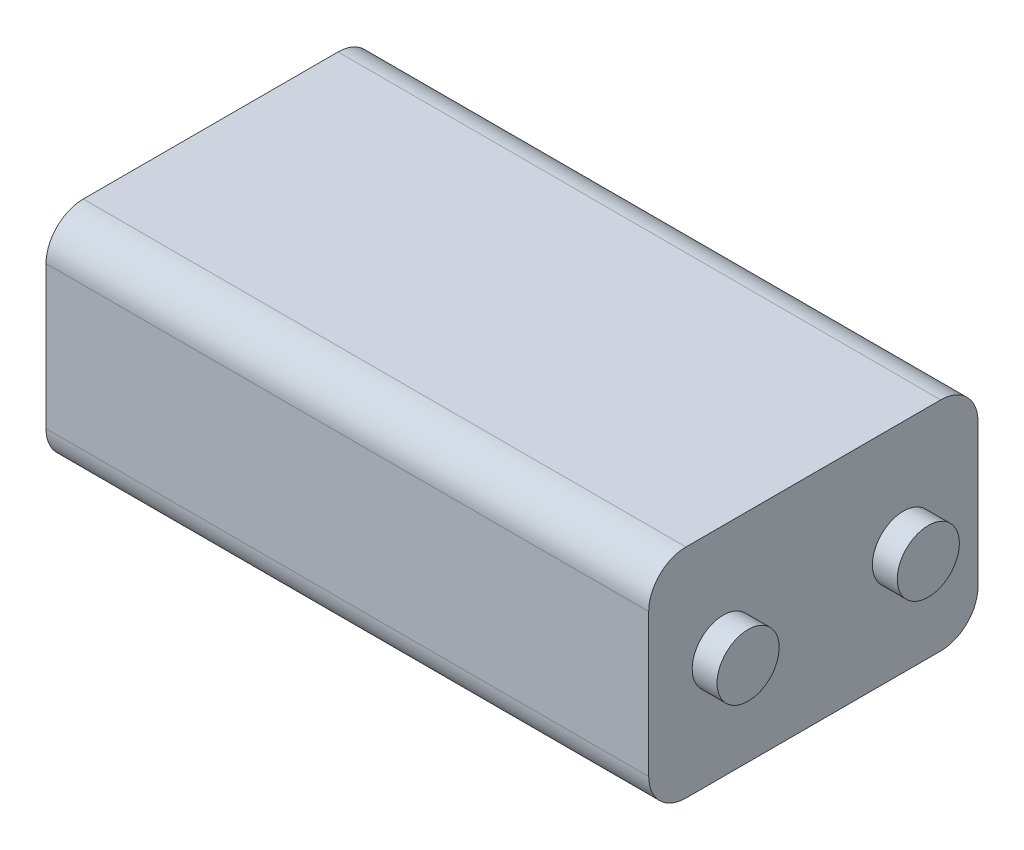
SolidWorks part; units mm, degrees
ref_plane "正面" through (0, 0, 0) normal (0, 0, 1) x (1, 0, 0)
ref_plane "平面" through (0, 0, 0) normal (0, 1, 0) x (1, 0, 0)
ref_plane "右側面" through (0, 0, 0) normal (1, 0, 0) x (0, 0, -1)
sketch "ｽｹｯﾁ1" plane through (0, 0, 0) normal (0, 0, 1) x (1, 0, 0)
  line L1 (-24.25, 8.75) -> (24.25, 8.75)
  line L2 (-24.25, 8.75) -> (-24.25, -8.75)
  line L3 (-24.25, -8.75) -> (24.25, -8.75)
  line L4 (24.25, 8.75) -> (24.25, -8.75)
  line L5 (-24.25, 8.75) -> (24.25, -8.75) construction
  line L6 (-24.25, -8.75) -> (24.25, 8.75) construction
  point P0 (0, 0)
  dimension "D1" = 48.5
  dimension "D2" = 17.5
extrude "ﾎﾞｽ - 押し出し1" add sketch "ｽｹｯﾁ1" along normal blind 26.5
fillet "ﾌｨﾚｯﾄ1" radius 3 4 edges at (0, -8.75, 26.5) (0, -8.75, 0) (0, 8.75, 0) (0, 8.75, 26.5)
sketch "ｽｹｯﾁ2" plane through (24.25, 0, 0) normal (1, 0, 0) x (0, 0, -1)
  line L0 (-26.5, -5.75) -> (-26.5, 5.75) construction
  line L1 (0, -5.75) -> (0, 5.75) construction
  circle A0 centre (-20.5, 0) radius 2.5
  circle A1 centre (-6, 0) radius 2.5
  point P6 (-26.5, 0)
  dimension "D1" = 6
  dimension "D2" = 6
  dimension "D5" = 5
  dimension "D6" = 5
  dimension "D3" = 0
  dimension "D4" = 0
extrude "ﾎﾞｽ - 押し出し2" add sketch "ｽｹｯﾁ2" along normal blind 2
